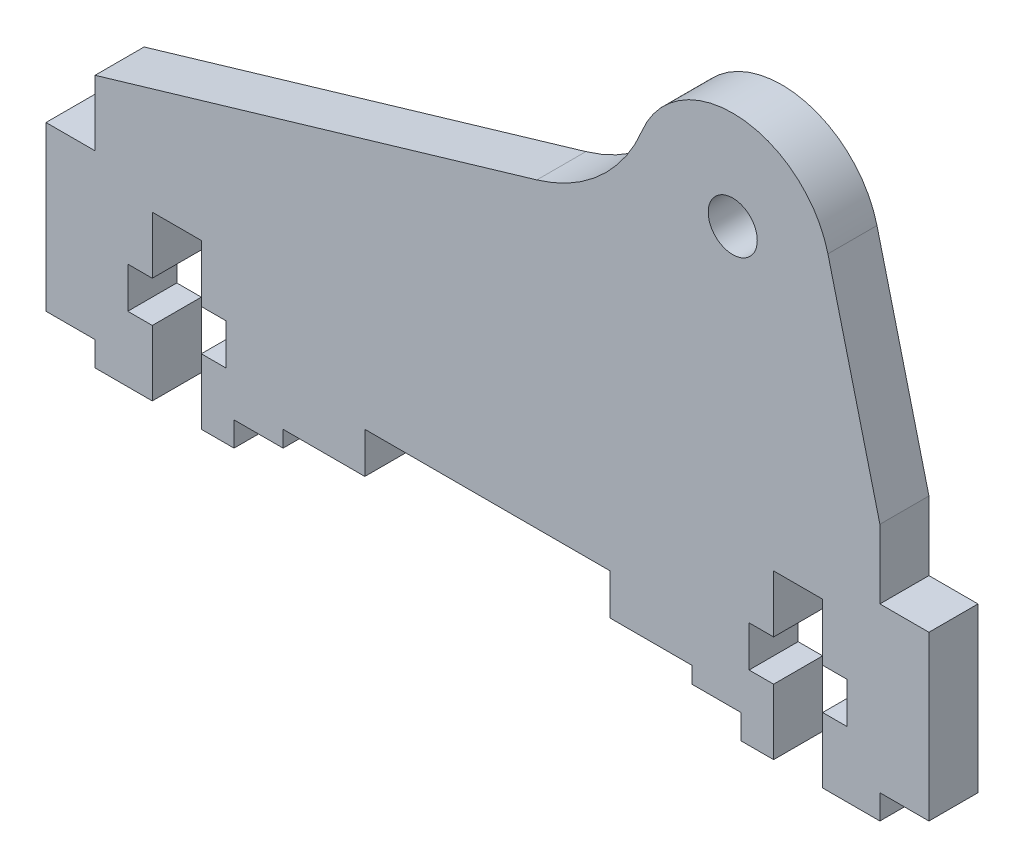
SolidWorks part; units mm, degrees
ref_plane "Plan de face" through (0, 0, 0) normal (0, 0, 1) x (1, 0, 0)
ref_plane "Plan de dessus" through (0, 0, 0) normal (0, 1, 0) x (1, 0, 0)
ref_plane "Plan de droite" through (0, 0, 0) normal (1, 0, 0) x (0, 0, -1)
sketch "Esquisse15" plane through (0, 0, 0) normal (0, 0, 1) x (1, 0, 0)
  line L0 (209.4243, 31.31) -> (211.4243, 31.31)
  line L1 (220.9243, 32.81) -> (217.9243, 32.81)
  line L2 (220.9243, 32.81) -> (220.9243, 42.81)
  line L3 (220.9243, 42.81) -> (217.9243, 42.81)
  line L4 (166.9243, 32.81) -> (166.9243, 42.81)
  line L5 (169.9243, 46.81) -> (196.9443, 54.7774)
  line L6 (169.9243, 42.81) -> (169.9243, 46.81)
  line L7 (176.4243, 37.81) -> (177.9243, 37.81)
  line L8 (217.9243, 42.81) -> (217.9243, 47.029)
  line L9 (169.9243, 31.31) -> (173.4243, 31.31)
  line L10 (169.9243, 31.31) -> (169.9243, 32.81)
  line L11 (201.4243, 33.81) -> (206.4243, 33.81)
  line L12 (217.9243, 31.31) -> (217.9243, 32.81)
  line L14 (178.4243, 31.31) -> (178.4243, 32.81)
  line L15 (178.4243, 32.81) -> (181.4243, 32.81)
  line L16 (209.4243, 31.31) -> (209.4243, 32.81)
  line L17 (186.4243, 33.81) -> (186.4243, 36.31)
  line L18 (181.4243, 32.81) -> (181.4243, 33.81)
  line L19 (181.4243, 33.81) -> (186.4243, 33.81)
  line L20 (206.4243, 32.81) -> (206.4243, 33.81)
  line L21 (206.4243, 32.81) -> (209.4243, 32.81)
  line L22 (169.9243, 32.81) -> (166.9243, 32.81)
  line L23 (169.9243, 42.81) -> (166.9243, 42.81)
  line L24 (186.4243, 36.31) -> (201.4243, 36.31)
  line L25 (201.4243, 33.81) -> (201.4243, 36.31)
  line L26 (217.9243, 47.029) -> (214.7457, 59.7631)
  line L28 (214.4243, 31.31) -> (214.4243, 35.31)
  line L29 (214.4243, 41.31) -> (211.4243, 41.31)
  line L30 (211.4243, 31.31) -> (211.4243, 35.31)
  line L31 (173.4243, 37.81) -> (173.4243, 41.31)
  line L32 (176.4243, 31.31) -> (176.4243, 35.31)
  line L33 (176.4243, 41.31) -> (173.4243, 41.31)
  line L34 (173.4243, 31.31) -> (173.4243, 35.31)
  line L35 (171.9243, 35.31) -> (173.4243, 35.31)
  line L36 (171.9243, 35.31) -> (171.9243, 37.81)
  line L37 (171.9243, 37.81) -> (173.4243, 37.81)
  line L38 (177.9243, 35.31) -> (177.9243, 37.81)
  line L39 (209.9243, 37.81) -> (211.4243, 37.81)
  line L40 (209.9243, 37.81) -> (209.9243, 35.31)
  line L41 (209.9243, 35.31) -> (211.4243, 35.31)
  line L42 (215.9243, 37.81) -> (215.9243, 35.31)
  line L43 (176.4243, 35.31) -> (177.9243, 35.31)
  line L44 (176.4243, 31.31) -> (178.4243, 31.31)
  line L45 (176.4243, 37.81) -> (176.4243, 41.31)
  line L46 (214.4243, 37.81) -> (215.9243, 37.81)
  line L47 (214.4243, 35.31) -> (215.9243, 35.31)
  line L48 (214.4243, 31.31) -> (217.9243, 31.31)
  line L49 (211.4243, 37.81) -> (211.4243, 41.31)
  line L50 (214.4243, 37.81) -> (214.4243, 41.31)
  circle A0 centre (208.9243, 58.31) radius 1.5
  arc A1 (214.7457, 59.7631) -> (203.3712, 60.5822) centre (208.9243, 58.31) ccw
  arc A2 (196.9443, 54.7774) -> (203.3712, 60.5822) centre (194.116, 64.3691) ccw
  dimension "D17" = 3
  dimension "D19" = 15.5
  dimension "D20" = 12
  dimension "D21" = 10
  dimension "D1" = 54
  dimension "D2" = 10
  dimension "D3" = 4
  dimension "D4" = 3
  dimension "D5" = 3
  dimension "D6" = 1.5
  dimension "D7" = 8.5
  dimension "D8" = 3
  dimension "D9" = 8.5
  dimension "D10" = 3
  dimension "D11" = 1
  dimension "D12" = 3
  dimension "D13" = 3
  dimension "D14" = 2.5
  dimension "D15" = 5
  dimension "D16" = 5
  dimension "D18" = 12
  dimension "D22" = 10
  dimension "D23" = 10
  dimension "D24" = 3
  dimension "D25" = 3
  dimension "D26" = 2
  dimension "D27" = 3.5
  dimension "D28" = 4
  dimension "D29" = 4
  dimension "D30" = 2.5
  dimension "D31" = 2.5
  dimension "D32" = 1.5
  dimension "D33" = 6
  dimension "D34" = 1.5
  dimension "D35" = 6
  dimension "D36" = 1.5
extrude "Boss.-Extru.15" add sketch "Esquisse15" along normal blind 3 separate body
